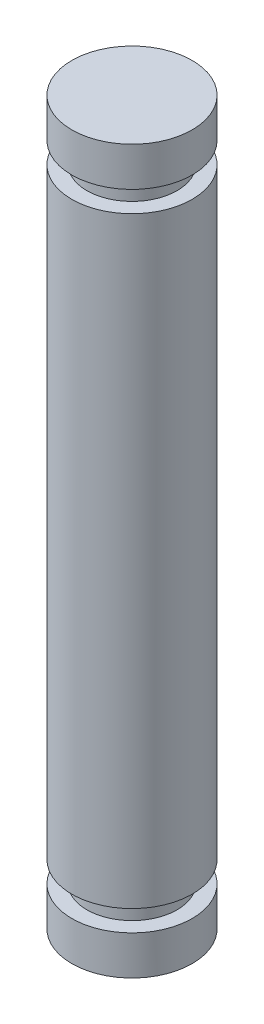
SolidWorks part; units mm, degrees
ref_plane "정면" through (0, 0, 0) normal (0, 0, 1) x (1, 0, 0)
ref_plane "윗면" through (0, 0, 0) normal (0, 1, 0) x (1, 0, 0)
ref_plane "우측면" through (0, 0, 0) normal (1, 0, 0) x (0, 0, -1)
sketch "스케치1" plane through (0, 0, 0) normal (0, 1, 0) x (1, 0, 0)
  circle A0 centre (0, 0) radius 2
  dimension "D1" = 4
extrude "보스-돌출1" add sketch "스케치1" along normal blind 24
sketch "스케치2" plane through (0, 24, 0) normal (0, 1, 0) x (1, 0, 0)
  circle A0 centre (0, 0) radius 2
  circle A1 centre (0, 0) radius 1.5
  dimension "D1" = 3
extrude "컷-돌출1" cut sketch "스케치2" against normal blind 0.7 from offset 1.3 offset against normal yes
sketch "스케치3" plane through (0, 0, 0) normal (0, -1, 0) x (1, 0, 0)
  circle A0 centre (0, 0) radius 2
  circle A1 centre (0, 0) radius 1.5
  dimension "D1" = 3
extrude "컷-돌출2" cut sketch "스케치3" against normal blind 0.7 from offset 1.3
